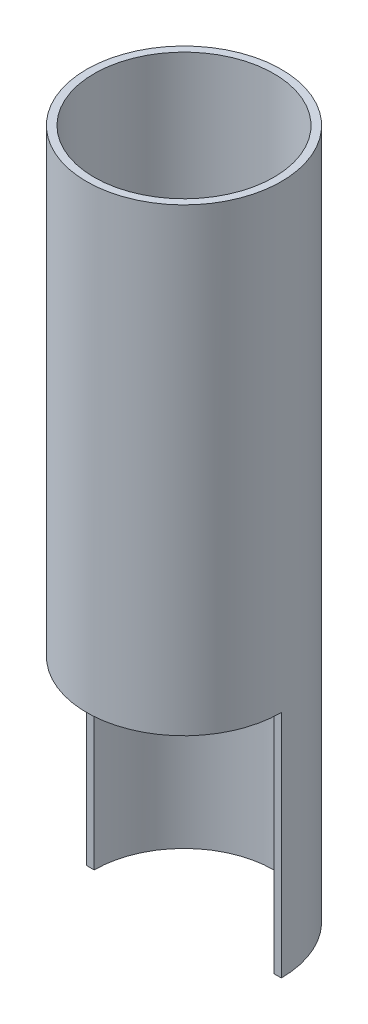
SolidWorks part; units mm, degrees
ref_plane "Front Plane" through (0, 0, 0) normal (0, 0, 1) x (1, 0, 0)
ref_plane "Top Plane" through (0, 0, 0) normal (0, 1, 0) x (1, 0, 0)
ref_plane "Right Plane" through (0, 0, 0) normal (1, 0, 0) x (0, 0, -1)
sketch "Sketch1" plane through (0, 0, 0) normal (0, 1, 0) x (1, 0, 0)
  circle A0 centre (0, 0) radius 25.4
  dimension "D1" = 50.8
extrude "Boss-Extrude1" add sketch "Sketch1" along normal blind 180 contours A0
sketch "Sketch2" plane through (0, 180, 0) normal (0, 1, 0) x (1, 0, 0)
  circle A0 centre (0, 0) radius 23.45
  dimension "D1" = 46.9
extrude "Cut-Extrude1" cut sketch "Sketch2" against normal blind 180
ref_plane "Plane1" through (0, 0, 50) normal (0, 0, 1) x (1, 0, 0)
sketch "Sketch4" plane through (0, 0, 50) normal (0, 0, 1) x (1, 0, 0)
  line L0 (0, 0) -> (0, 106.6738) construction
  line L1 (-25.4, 0) -> (25.4, 0) construction
  line L2 (-39.9, 60) -> (39.9, 60)
  line L3 (-39.9, 60) -> (-39.9, 0)
  line L4 (-39.9, 0) -> (39.9, 0)
  line L5 (39.9, 60) -> (39.9, 0)
  line L6 (-39.9, 60) -> (39.9, 0) construction
  line L7 (-39.9, 0) -> (39.9, 60) construction
  point P3 (0, 30)
  dimension "D1" = 79.8
  dimension "D2" = 60
extrude "Cut-Extrude2" cut sketch "Sketch4" against normal blind 50
